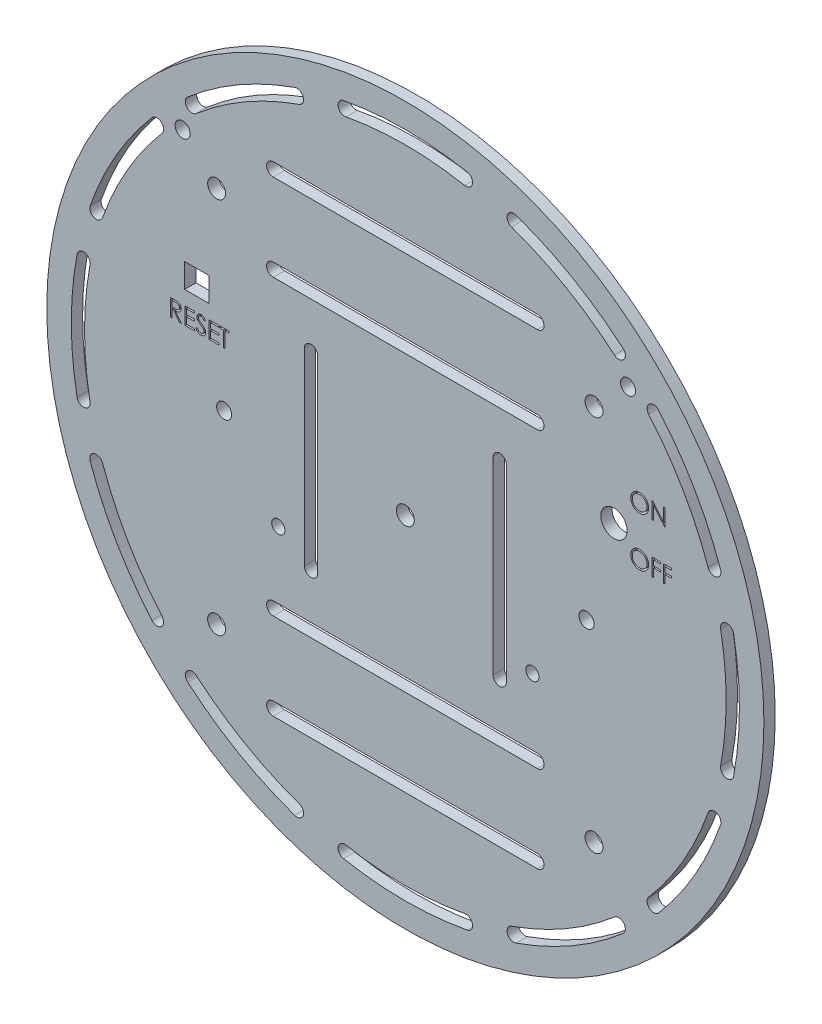
SolidWorks part; units mm, degrees
ref_plane "Alzado" through (0, 0, 0) normal (0, 0, 1) x (1, 0, 0)
ref_plane "Planta" through (0, 0, 0) normal (0, 1, 0) x (1, 0, 0)
ref_plane "Vista lateral" through (0, 0, 0) normal (1, 0, 0) x (0, 0, -1)
sketch "Croquis1" plane through (0, 0, 0) normal (0, 0, 1) x (1, 0, 0)
  line L3 (0, 0) -> (0, 95) construction
  line L7 (0, 0) -> (0, -95) construction
  line L8 (25, 60.1103) -> (35, 60.1103)
  line L19 (25, -40.6103) -> (35, -40.6103)
  line L25 (0, 0) -> (-47.5, -82.2724) construction
  line L26 (-35, -38.8603) -> (35, -38.8603) construction
  line L27 (0, 0) -> (-82.2724, -47.5) construction
  line L28 (0, 0) -> (-95, 0) construction
  line L29 (0, 0) -> (-82.2724, 47.5) construction
  line L30 (0, 0) -> (-47.5, 82.2724) construction
  line L31 (0, 0) -> (0, 95) construction
  line L32 (0, 0) -> (47.5, 82.2724) construction
  line L33 (0, 0) -> (82.2724, 47.5) construction
  line L34 (0, 0) -> (95, 0) construction
  line L35 (0, 0) -> (82.2724, -47.5) construction
  line L36 (0, 0) -> (47.5, -82.2724) construction
  line L39 (-35, -37.1103) -> (35, -37.1103)
  line L40 (-35, -40.6103) -> (19, -40.6103)
  line L41 (0, 0) -> (61.8321, 58.3249) construction
  line L44 (-35, -61.8603) -> (35, -61.8603) construction
  line L53 (-35, -60.1103) -> (19, -60.1103)
  line L54 (-35, -63.6103) -> (35, -63.6103)
  line L58 (-35, 63.6103) -> (35, 63.6103)
  line L61 (-25, -25) -> (-25, 25) construction
  line L62 (-26.75, -25) -> (-26.75, 25)
  line L63 (-23.25, -25) -> (-23.25, 25)
  line L64 (25, -25) -> (25, 25) construction
  line L65 (26.75, -25) -> (26.75, 25)
  line L66 (23.25, -25) -> (23.25, 25)
  line L82 (25, -60.1103) -> (35, -60.1103)
  line L83 (-35, 60.1103) -> (19, 60.1103)
  line L90 (-35, 40.6103) -> (19, 40.6103)
  line L91 (-35, 37.1103) -> (35, 37.1103)
  line L92 (25, 40.6103) -> (35, 40.6103)
  line L93 (19, 60.1103) -> (25, 60.1103)
  line L94 (19, 40.6103) -> (25, 40.6103)
  line L95 (19, -40.6103) -> (25, -40.6103)
  line L96 (19, -60.1103) -> (25, -60.1103)
  line L98 (-58.4718, 22.5933) -> (-52.0718, 22.5933)
  line L99 (-58.4718, 22.5933) -> (-58.4718, 28.9933)
  line L100 (-58.4718, 28.9933) -> (-52.0718, 28.9933)
  line L101 (-52.0718, 22.5933) -> (-52.0718, 28.9933)
  line L102 (-58.4718, 22.5933) -> (-52.0718, 28.9933) construction
  line L103 (-58.4718, 28.9933) -> (-52.0718, 22.5933) construction
  arc A0 (-73.6546, -60) -> (73.6546, -60) centre (0, 0) ccw
  arc A5 (94.4722, 10) -> (-94.4722, 10) centre (0, 0) ccw
  circle A67 centre (-59, 59) radius 2
  arc A68 (28.133, 80.2093) -> (29.2914, 83.512) centre (28.7122, 81.8607) cw
  arc A69 (57.6778, 67.1232) -> (29.2914, 83.512) centre (0, 0) ccw
  arc A70 (55.3968, 64.4686) -> (57.6778, 67.1232) centre (56.5373, 65.7959) ccw
  arc A71 (55.3968, 64.4686) -> (28.133, 80.2093) centre (0, 0) ccw
  arc A72 (64.4686, 55.3968) -> (67.1232, 57.6778) centre (65.7959, 56.5373) cw
  arc A73 (83.512, 29.2914) -> (67.1232, 57.6778) centre (0, 0) ccw
  arc A74 (80.2093, 28.133) -> (83.512, 29.2914) centre (81.8607, 28.7122) ccw
  arc A75 (80.2093, 28.133) -> (64.4686, 55.3968) centre (0, 0) ccw
  arc A76 (83.5298, 15.7407) -> (86.9693, 16.3889) centre (85.2495, 16.0648) cw
  arc A77 (86.9693, -16.3889) -> (86.9693, 16.3889) centre (0, 0) ccw
  arc A78 (83.5298, -15.7407) -> (86.9693, -16.3889) centre (85.2495, -16.0648) ccw
  arc A79 (83.5298, -15.7407) -> (83.5298, 15.7407) centre (0, 0) ccw
  arc A80 (80.2093, -28.133) -> (83.512, -29.2914) centre (81.8607, -28.7122) cw
  arc A81 (67.1232, -57.6778) -> (83.512, -29.2914) centre (0, 0) ccw
  arc A82 (64.4686, -55.3968) -> (67.1232, -57.6778) centre (65.7959, -56.5373) ccw
  arc A83 (64.4686, -55.3968) -> (80.2093, -28.133) centre (0, 0) ccw
  arc A84 (55.3968, -64.4686) -> (57.6778, -67.1232) centre (56.5373, -65.7959) cw
  arc A85 (29.2914, -83.512) -> (57.6778, -67.1232) centre (0, 0) ccw
  arc A86 (28.133, -80.2093) -> (29.2914, -83.512) centre (28.7122, -81.8607) ccw
  circle A87 centre (-50, 50) radius 2.375
  arc A90 (-35, -37.1103) -> (-35, -40.6103) centre (-35, -38.8603) ccw
  arc A91 (35, -40.6103) -> (35, -37.1103) centre (35, -38.8603) ccw
  circle A98 centre (-50, -50) radius 2.375
  circle A99 centre (50, -50) radius 2.375
  circle A100 centre (50, 50) radius 2.375
  arc A111 (-35, -60.1103) -> (-35, -63.6103) centre (-35, -61.8603) ccw
  arc A112 (35, -63.6103) -> (35, -60.1103) centre (35, -61.8603) ccw
  circle A113 centre (55.2718, 25.7933) radius 3.5
  arc A124 (-26.75, -25) -> (-23.25, -25) centre (-25, -25) ccw
  arc A125 (-23.25, 25) -> (-26.75, 25) centre (-25, 25) ccw
  arc A126 (26.75, -25) -> (23.25, -25) centre (25, -25) cw
  arc A127 (23.25, 25) -> (26.75, 25) centre (25, 25) cw
  circle A128 centre (-55.2718, 25.7933) radius 3.5 construction
  circle A135 centre (0, 0) radius 95 construction
  arc A136 (-94.4722, 10) -> (-73.6546, -60) centre (0, 0) ccw
  arc A137 (94.4722, 10) -> (73.6546, -60) centre (0, 0) cw
  arc A138 (28.133, -80.2093) -> (55.3968, -64.4686) centre (0, 0) ccw
  arc A139 (15.7407, -83.5298) -> (16.3889, -86.9693) centre (16.0648, -85.2495) cw
  arc A140 (-16.3889, -86.9693) -> (16.3889, -86.9693) centre (0, 0) ccw
  arc A141 (-15.7407, -83.5298) -> (-16.3889, -86.9693) centre (-16.0648, -85.2495) ccw
  arc A142 (-15.7407, -83.5298) -> (15.7407, -83.5298) centre (0, 0) ccw
  arc A143 (-28.133, -80.2093) -> (-29.2914, -83.512) centre (-28.7122, -81.8607) cw
  arc A144 (-57.6778, -67.1232) -> (-29.2914, -83.512) centre (0, 0) ccw
  arc A145 (-55.3968, -64.4686) -> (-57.6778, -67.1232) centre (-56.5373, -65.7959) ccw
  arc A146 (-55.3968, -64.4686) -> (-28.133, -80.2093) centre (0, 0) ccw
  arc A147 (-64.4686, -55.3968) -> (-67.1232, -57.6778) centre (-65.7959, -56.5373) cw
  arc A148 (-83.512, -29.2914) -> (-67.1232, -57.6778) centre (0, 0) ccw
  arc A149 (-80.2093, -28.133) -> (-83.512, -29.2914) centre (-81.8607, -28.7122) ccw
  arc A150 (-80.2093, -28.133) -> (-64.4686, -55.3968) centre (0, 0) ccw
  arc A151 (-83.5298, -15.7407) -> (-86.9693, -16.3889) centre (-85.2495, -16.0648) cw
  arc A152 (-86.9693, 16.3889) -> (-86.9693, -16.3889) centre (0, 0) ccw
  arc A153 (-83.5298, 15.7407) -> (-86.9693, 16.3889) centre (-85.2495, 16.0648) ccw
  arc A154 (-83.5298, 15.7407) -> (-83.5298, -15.7407) centre (0, 0) ccw
  arc A155 (-80.2093, 28.133) -> (-83.512, 29.2914) centre (-81.8607, 28.7122) cw
  arc A156 (-67.1232, 57.6778) -> (-83.512, 29.2914) centre (0, 0) ccw
  arc A157 (-64.4686, 55.3968) -> (-67.1232, 57.6778) centre (-65.7959, 56.5373) ccw
  arc A158 (-64.4686, 55.3968) -> (-80.2093, 28.133) centre (0, 0) ccw
  arc A159 (-55.3968, 64.4686) -> (-57.6778, 67.1232) centre (-56.5373, 65.7959) cw
  arc A160 (-29.2914, 83.512) -> (-57.6778, 67.1232) centre (0, 0) ccw
  arc A161 (-28.133, 80.2093) -> (-29.2914, 83.512) centre (-28.7122, 81.8607) ccw
  arc A182 (-15.7407, 83.5298) -> (-16.3889, 86.9693) centre (-16.0648, 85.2495) cw
  arc A183 (16.3889, 86.9693) -> (-16.3889, 86.9693) centre (0, 0) ccw
  arc A184 (15.7407, 83.5298) -> (16.3889, 86.9693) centre (16.0648, 85.2495) ccw
  arc A185 (15.7407, 83.5298) -> (-15.7407, 83.5298) centre (0, 0) ccw
  circle A217 centre (48, 0) radius 2
  circle A218 centre (-48, 0) radius 2
  arc A219 (35, 63.6103) -> (35, 60.1103) centre (35, 61.8603) cw
  arc A220 (-35, 60.1103) -> (-35, 63.6103) centre (-35, 61.8603) cw
  arc A221 (-35, 37.1103) -> (-35, 40.6103) centre (-35, 38.8603) cw
  arc A222 (35, 40.6103) -> (35, 37.1103) centre (35, 38.8603) cw
  circle A223 centre (0, 0) radius 38.8603 construction
  circle A224 centre (0, 38.8603) radius 1.75 construction
  circle A225 centre (33.654, -19.4302) radius 1.75
  circle A226 centre (-33.654, -19.4302) radius 1.75
  circle A227 centre (0, 0) radius 2.375
  arc A228 (-28.133, 80.2093) -> (-55.3968, 64.4686) centre (0, 0) ccw
  circle A229 centre (59, 59) radius 2
  point P62 (0, -38.8603)
  point P98 (0, -61.8603)
  point P135 (0, 0)
  point P136 (0, 0)
  point P203 (0, 27.661)
  point P230 (-25, 0)
  point P237 (25, 0)
  point P250 (0, 0)
  dimension "D6" = 88.5
  dimension "D7" = 4.75
  dimension "D8" = 85
  dimension "D13" = 59
  dimension "D14" = 6.4
  dimension "D24" = 50
  dimension "D25" = 4.75
  dimension "D32" = 3.5
  dimension "D42" = 7
  dimension "D9" = 59
  dimension "D10" = 4
  dimension "D12" = 6.4
  dimension "D19" = 3
  dimension "D16" = 4
  dimension "D11" = 48
  dimension "D15" = 25
  dimension "D17" = 12
  dimension "D22" = 12
  dimension "D23" = 50
  dimension "D27" = 70
  dimension "D28" = 3.5
  dimension "D33" = 23
  dimension "D45" = 25
  dimension "D55" = 50
  dimension "D56" = 3.5
extrude "Saliente-Extruir1" add sketch "Croquis1" along normal blind 3
sketch "Croquis2" plane through (0, 0, 3) normal (0, 0, 1) x (1, 0, 0)
  line L0 (59.3683, 31.6313) -> (73.7061, 31.6313) construction
  line L1 (59.3683, 18.5949) -> (81.4573, 18.5949) construction
  line L2 (-69.339, 30.9684) -> (-51.1795, 30.9684) construction
  line L3 (-62.8066, 14.3688) -> (-43.243, 14.3688) construction
  text T0 "ON" font "Century Gothic" height 4.5
  text T1 "OFF" font "Century Gothic" height 4.5
  text T2 "RESET\r\n" font "Century Gothic" height 4.5
extrude "Cortar-Extruir2" cut sketch "Croquis2" against normal blind 2
